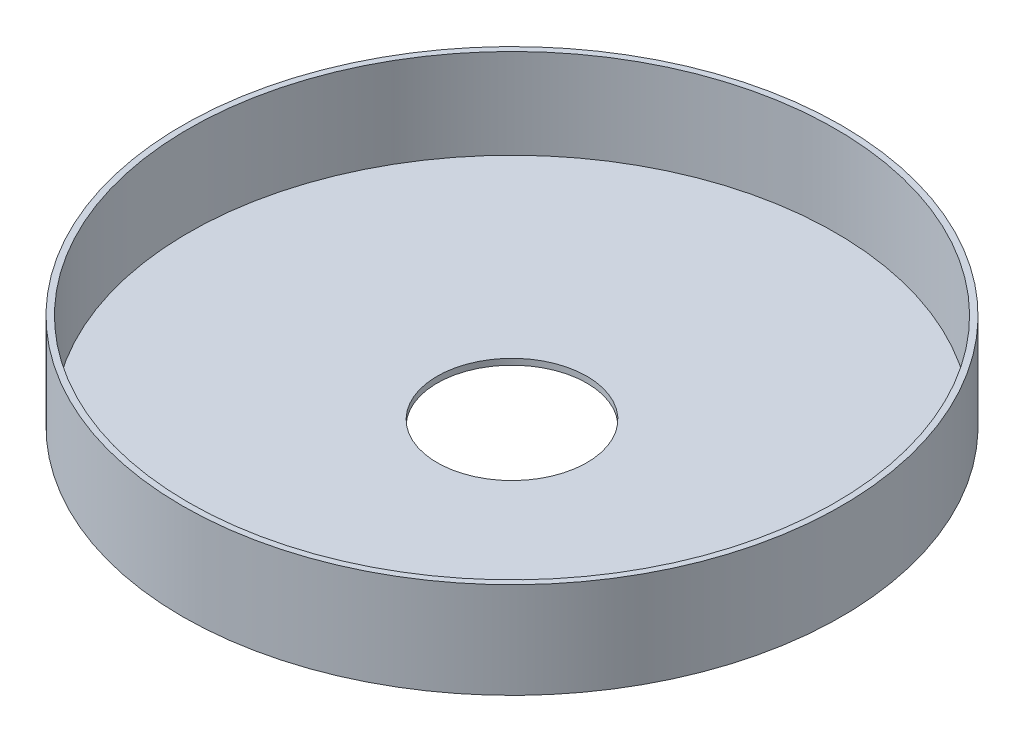
SolidWorks part; units mm, degrees
ref_plane "Front Plane" through (0, 0, 0) normal (0, 0, 1) x (1, 0, 0)
ref_plane "Top Plane" through (0, 0, 0) normal (0, 1, 0) x (1, 0, 0)
ref_plane "Right Plane" through (0, 0, 0) normal (1, 0, 0) x (0, 0, -1)
sketch "Sketch1" plane through (0, 0, 0) normal (0, 1, 0) x (1, 0, 0)
  circle A0 centre (0, 0) radius 54
  circle A1 centre (0, 0) radius 55
  dimension "D1" = 1
  dimension "D2" = 108
extrude "Boss-Extrude1" add sketch "Sketch1" along normal blind 15
sketch "Sketch2" plane through (0, 0, 0) normal (0, -1, 0) x (1, 0, 0)
  circle A0 centre (0, 0) radius 55
  circle A1 centre (0, 0) radius 12.5
  circle A2 centre (0, 0) radius 55 construction
  dimension "D1" = 25
extrude "Boss-Extrude2" add sketch "Sketch2" along normal blind 1
